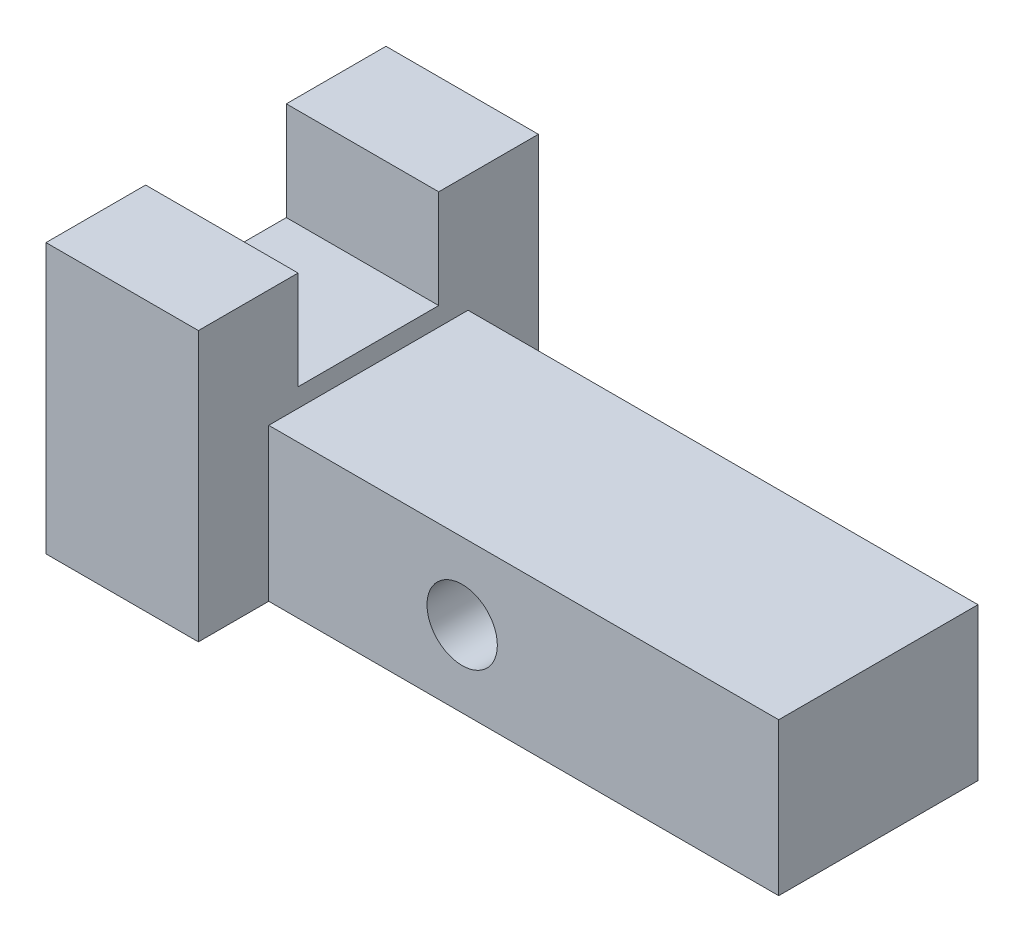
SolidWorks part; units mm, degrees
ref_plane "정면" through (0, 0, 0) normal (0, 0, 1) x (1, 0, 0)
ref_plane "윗면" through (0, 0, 0) normal (0, 1, 0) x (1, 0, 0)
ref_plane "우측면" through (0, 0, 0) normal (1, 0, 0) x (0, 0, -1)
sketch "스케치1" plane through (0, 0, 0) normal (1, 0, 0) x (0, 0, -1)
  line L0 (-29, 0) -> (29, 0)
  line L1 (29, 46) -> (12, 46)
  line L2 (12, 46) -> (12, 29.1921)
  line L3 (12, 29.1921) -> (-12, 29.1921)
  line L4 (-12, 29.1921) -> (-12, 46)
  line L5 (-12, 46) -> (-29, 46)
  line L6 (-29, 46) -> (-29, 0)
  line L7 (29, 0) -> (29, 46)
  dimension "D1" = 46
  dimension "D2" = 58
  dimension "D3" = 17
  dimension "D4" = 24
  dimension "D5" = 46
extrude "보스-돌출1" add sketch "스케치1" along normal blind 26
sketch "스케치2" plane through (0, 0, 0) normal (0, 0, 1) x (1, 0, 0)
  line L1 (26, 0) -> (113, 0)
  line L2 (26, 0) -> (26, 26)
  line L3 (26, 26) -> (113, 26)
  line L4 (113, 0) -> (113, 26)
  circle A0 centre (59, 13) radius 6
  dimension "D2" = 12
  dimension "D1" = 113
  dimension "D3" = 59
  dimension "D4" = 26
  dimension "D5" = 13
extrude "보스-돌출2" add sketch "스케치2" along normal mid plane 34
